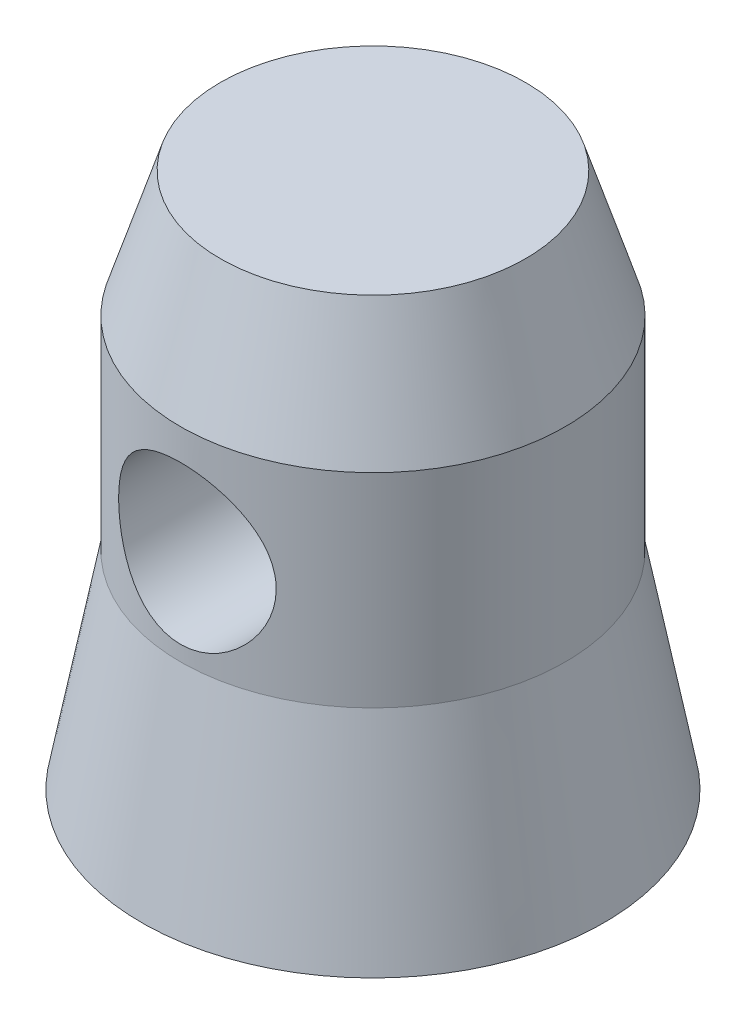
SolidWorks part; units mm, degrees
material "6061-T6 (SS)"
ref_plane "Front" through (0, 0, 0) normal (0, 0, 1) x (1, 0, 0)
ref_plane "Top" through (0, 0, 0) normal (0, 1, 0) x (1, 0, 0)
ref_plane "Right" through (0, 0, 0) normal (1, 0, 0) x (0, 0, -1)
sketch "Sketch1" plane through (0, 0, 0) normal (0, 0, 1) x (1, 0, 0)
  line L0 (0, 40.0685) -> (0, 3.31)
  line L1 (0, -50) -> (0, 50) construction
  line L2 (0, 40.0685) -> (11.4173, 40.0685)
  line L3 (11.4173, 40.0685) -> (14.3891, 30.672)
  line L4 (14.3891, 30.672) -> (14.3891, 15.432)
  line L5 (14.3891, 15.432) -> (17.2974, 0)
  line L6 (50, 0) -> (-50, 0) construction
  line L7 (10.5974, 0) -> (5, 3.31)
  line L8 (10.5974, 0) -> (17.2974, 0)
  line L9 (5, 3.31) -> (0, 3.31)
  point P0 (0, 0)
  dimension "D1" = 40.0685
  dimension "D2" = 6.7
  dimension "D3" = 3.31
  dimension "D4" = 11.4173
  dimension "D5" = 15.24
  dimension "D6" = 9.8552
  dimension "D7" = 5
  dimension "D8" = 17.2974
  dimension "D9" = 14.3891
revolve "Revolve1" add sketch "Sketch1" angle 360 about L0
sketch "Sketch2" plane through (0, 0, 0) normal (0, 0, 1) x (1, 0, 0)
  line L0 (0, 30.672) -> (0, 40.0685) construction
  line L1 (11.4173, 40.0685) -> (-11.4173, 40.0685) construction
  circle A0 centre (0, 22.4663) radius 5.8928
  dimension "D1" = 17.6022
  dimension "D2" = 11.7856
extrude "Cut-Extrude1" cut sketch "Sketch2" against normal through all and the other way through all
hole_wizard "M10x1.5 Tapped Hole1" positions "Sketch4" profile "Sketch5" tap size "M10x1.5" standard "ANSI Metric"
sketch "Sketch4" plane through (0, 3.31, 0) normal (0, -1, 0) x (-1, 0, 0)
  point P0 (0, 0)
sketch "Sketch5" plane through (0, 3.31, 0) normal (1, 0, 0) x (0, 0, -1)
  line L0 (0, 0) -> (0, 11.7993)
  line L1 (0, 11.7993) -> (4.25, 9.2456)
  line L2 (4.25, 9.2456) -> (4.25, 0)
  line L5 (4.25, 0) -> (0, 0)
  line L10 (0, 11.7993) -> (-4.25, 9.2456) construction
  line L11 (0, -6.35) -> (0, 107.95) construction
  dimension "Tap Drill Dia." = 8.5
  dimension "Tap Drill Depth" = 9.2456
  dimension "Drill Angle" = 118
cosmetic thread "Hole Thread1" parameters "D1"=7.2898, "D2"=10
